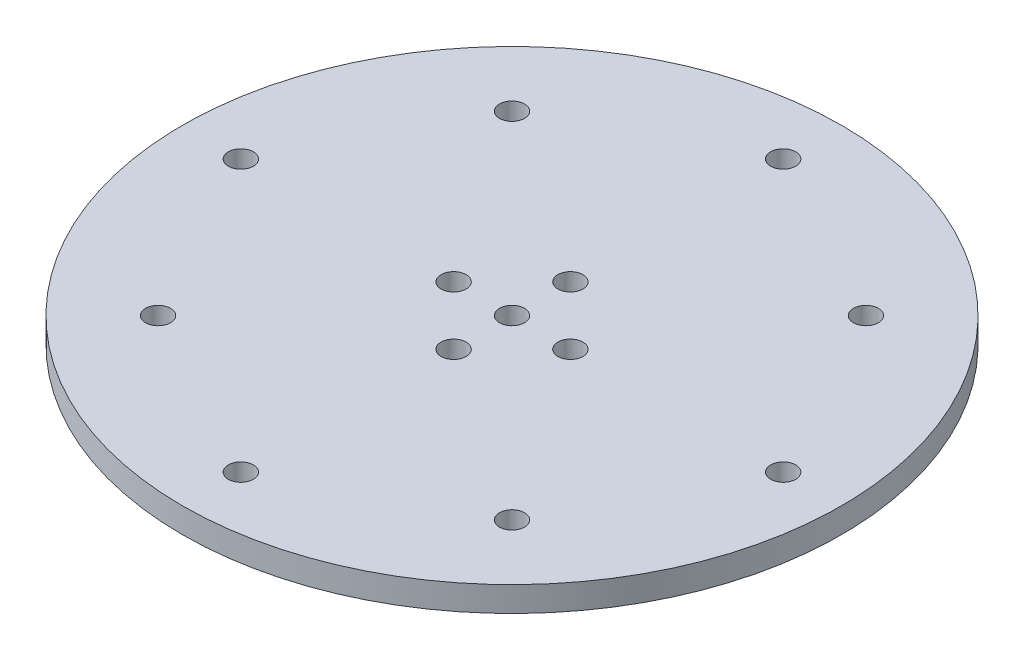
SolidWorks part; units mm, degrees
ref_plane "前视基准面" through (0, 0, 0) normal (0, 0, 1) x (1, 0, 0)
ref_plane "上视基准面" through (0, 0, 0) normal (0, 1, 0) x (1, 0, 0)
ref_plane "右视基准面" through (0, 0, 0) normal (1, 0, 0) x (0, 0, -1)
other "Configuration Table"
sketch "草图1" plane through (0, 0, 0) normal (0, 1, 0) x (1, 0, 0)
  line L0 (0, 0) -> (22.5805, 0) construction
  line L1 (0, 0) -> (46.0854, 46.0854) construction
  circle A0 centre (0, 0) radius 39.5
  circle A1 centre (0, 0) radius 32.5 construction
  circle A2 centre (0, 32.5) radius 1.5
  circle A3 centre (0, 0) radius 32.5 construction
  circle A4 centre (32.5, 0) radius 1.5
  circle A5 centre (0, 0) radius 32.5 construction
  circle A6 centre (0, -32.5) radius 1.5
  circle A7 centre (0, 0) radius 32.5 construction
  circle A8 centre (-32.5, 0) radius 1.5
  circle A9 centre (0, 0) radius 30 construction
  circle A10 centre (21.2132, 21.2132) radius 1.5
  circle A11 centre (21.2132, -21.2132) radius 1.5
  circle A12 centre (-21.2132, -21.2132) radius 1.5
  circle A13 centre (-21.2132, 21.2132) radius 1.5
  point P18 (0, 0)
  point P30 (0, 0)
  dimension "D1" = 79
  dimension "D2" = 65
  dimension "D3" = 3
  dimension "D5" = 60
  dimension "D7" = 3
  dimension "D6" = 45
  dimension "D4" = 4
  dimension "D8" = 4
extrude "凸台-拉伸1" add sketch "草图1" along normal blind 3
sketch "草图2" plane through (0, 3, 0) normal (0, 1, 0) x (1, 0, 0)
  circle A0 centre (0, 0) radius 1.5
  circle A1 centre (0, 0) radius 7 construction
  circle A2 centre (0, 7) radius 1.5
  circle A3 centre (7, 0) radius 1.5
  circle A4 centre (0, -7) radius 1.5
  circle A5 centre (-7, 0) radius 1.5
  point P15 (0, 0)
  dimension "D1" = 3
  dimension "D2" = 14
  dimension "D3" = 3
  dimension "D4" = 4
extrude "切除-拉伸1" cut sketch "草图2" against normal through all both and the other way through all
